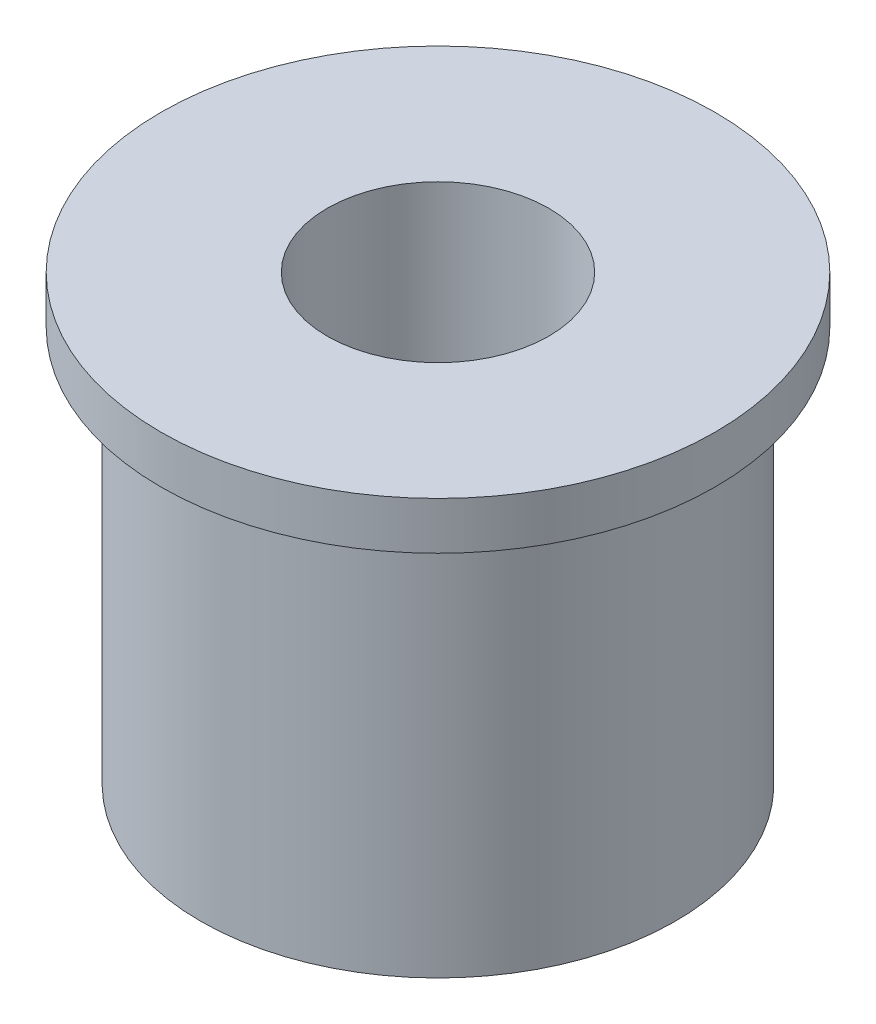
SolidWorks part; units mm, degrees
ref_plane "Front Plane" through (0, 0, 0) normal (0, 0, 1) x (1, 0, 0)
ref_plane "Top Plane" through (0, 0, 0) normal (0, 1, 0) x (1, 0, 0)
ref_plane "Right Plane" through (0, 0, 0) normal (1, 0, 0) x (0, 0, -1)
sketch "Sketch1" plane through (0, 0, 0) normal (0, 1, 0) x (1, 0, 0)
  circle A0 centre (0, 0) radius 3
  circle A1 centre (0, 0) radius 1.4
  dimension "D1" = 6
  dimension "D2" = 2.8
extrude "Boss-Extrude1" add sketch "Sketch1" along normal blind 5
sketch "Sketch2" plane through (0, 5, 0) normal (0, 1, 0) x (1, 0, 0)
  circle A0 centre (0, 0) radius 3.5
  circle A1 centre (0, 0) radius 1.4
  circle A2 centre (0, 0) radius 1.4 construction
  dimension "D1" = 7
extrude "Boss-Extrude2" add sketch "Sketch2" along normal blind 0.6
